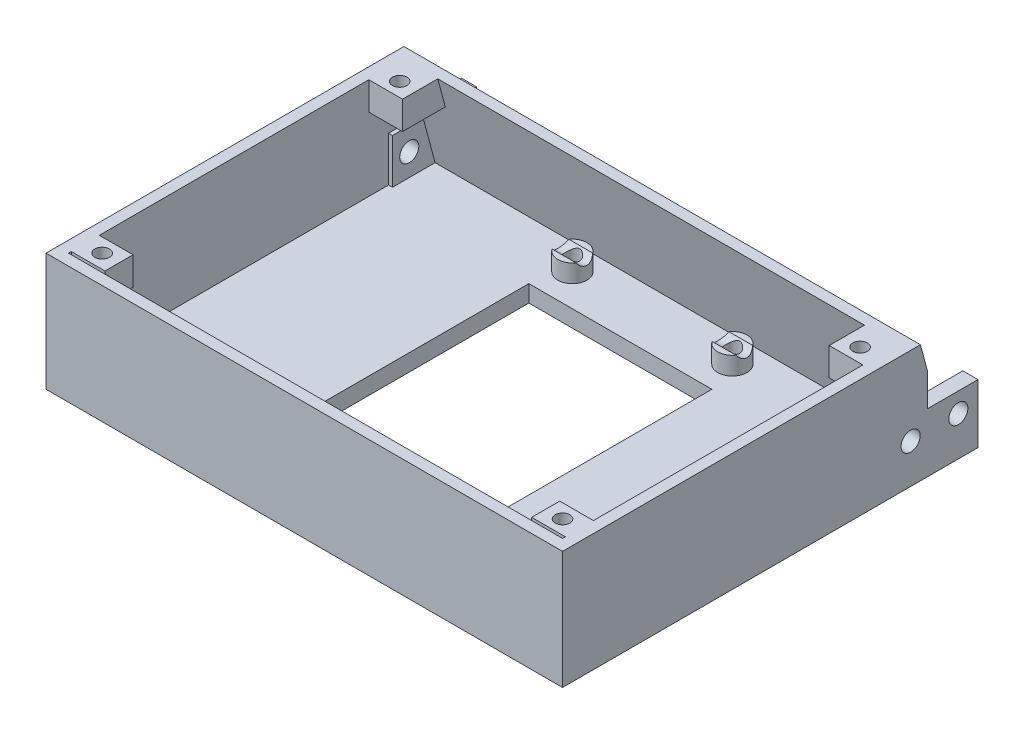
SolidWorks part; units mm, degrees
ref_plane "Спереди" through (0, 0, 0) normal (0, 0, 1) x (1, 0, 0)
ref_plane "Сверху" through (0, 0, 0) normal (0, 1, 0) x (1, 0, 0)
ref_plane "Справа" through (0, 0, 0) normal (1, 0, 0) x (0, 0, -1)
other "Configuration Table"
ref_plane "Плоскость1" through (0, 0, 55) normal (0, 0, 1) x (1, 0, 0)
sketch "Эскиз1" plane through (0, 0, 55) normal (0, 0, 1) x (1, 0, 0)
  line L1 (-46, -67) -> (46, -67)
  line L2 (-46, -67) -> (-46, -64)
  line L3 (-46, -64) -> (46, -64)
  line L4 (46, -67) -> (46, -64)
extrude "Front_panel_1" add sketch "Эскиз1" along normal blind 65
ref_plane "Плоскость2" through (0, -68, 0) normal (0, 1, 0) x (1, 0, 0)
sketch "Эскиз2" plane through (0, -68, 0) normal (0, 1, 0) x (1, 0, 0)
  line L1 (-16.3, -63.7) -> (16.3, -63.7)
  line L2 (-16.3, -63.7) -> (-16.3, -106.3)
  line L3 (-16.3, -106.3) -> (16.3, -106.3)
  line L4 (16.3, -63.7) -> (16.3, -106.3)
extrude "STEP_portrait_LCD_window_32_6x42_6_2" cut sketch "Эскиз2" along normal blind 5
ref_plane "Плоскость3" through (0, -68, 0) normal (0, 1, 0) x (1, 0, 0)
sketch "Эскиз3" plane through (0, -68, 0) normal (0, 1, 0) x (1, 0, 0)
  circle A0 centre (38, -77) radius 3.3
extrude "Button_bore_3" cut sketch "Эскиз3" along normal blind 5
ref_plane "Плоскость4" through (0, -64, 0) normal (0, 1, 0) x (1, 0, 0)
sketch "Эскиз4" plane through (0, -64, 0) normal (0, 1, 0) x (1, 0, 0)
  circle A0 centre (-14.25, -58) radius 2.6
  circle A1 centre (-14.25, -110) radius 2.6
  circle A2 centre (14.25, -58) radius 2.6
  circle A3 centre (14.25, -110) radius 2.6
extrude "Four_M3_PCB_standoffs_4" add sketch "Эскиз4" along normal blind 3.2
ref_plane "Плоскость5" through (0, -68, 0) normal (0, 1, 0) x (1, 0, 0)
sketch "Эскиз5" plane through (0, -68, 0) normal (0, 1, 0) x (1, 0, 0)
  circle A0 centre (-14.25, -58) radius 1.3
  circle A1 centre (14.25, -58) radius 1.3
  circle A2 centre (-14.25, -110) radius 1.3
  circle A3 centre (14.25, -110) radius 1.3
extrude "M3_PCB_mount_pilots_52x28_5_5" cut sketch "Эскиз5" along normal blind 9
ref_plane "Плоскость6" through (0, 0, 55) normal (0, 0, 1) x (1, 0, 0)
sketch "Эскиз6" plane through (0, 0, 55) normal (0, 0, 1) x (1, 0, 0)
  line L1 (-46, -64) -> (-44, -64)
  line L2 (-46, -64) -> (-46, -46)
  line L3 (-46, -46) -> (-44, -46)
  line L4 (-44, -64) -> (-44, -46)
extrude "Housing_left_6" add sketch "Эскиз6" along normal blind 65
ref_plane "Плоскость7" through (0, 0, 55) normal (0, 0, 1) x (1, 0, 0)
sketch "Эскиз7" plane through (0, 0, 55) normal (0, 0, 1) x (1, 0, 0)
  line L0 (46, -64) -> (-44, -64) construction
  line L1 (44, -64) -> (46, -64)
  line L2 (44, -64) -> (44, -46)
  line L3 (44, -46) -> (46, -46)
  line L4 (46, -64) -> (46, -46)
extrude "Housing_right_7" add sketch "Эскиз7" along normal blind 65
ref_plane "Плоскость8" through (0, 0, 55) normal (0, 0, 1) x (1, 0, 0)
sketch "Эскиз8" plane through (0, 0, 55) normal (0, 0, 1) x (1, 0, 0)
  line L1 (-44, -64) -> (44, -64)
  line L2 (-44, -64) -> (-44, -46)
  line L3 (-44, -46) -> (44, -46)
  line L4 (44, -64) -> (44, -46)
ref_plane "Плоскость9" through (0, 0, 118) normal (0, 0, 1) x (1, 0, 0)
sketch "Эскиз9" plane through (0, 0, 118) normal (0, 0, 1) x (1, 0, 0)
  line L1 (-44, -64) -> (44, -64)
  line L2 (-44, -64) -> (-44, -46)
  line L3 (-44, -46) -> (44, -46)
  line L4 (44, -64) -> (44, -46)
extrude "Housing_top_9" add sketch "Эскиз9" along normal blind 2
ref_plane "Плоскость10" through (0, 0, 55.5) normal (0, 0, 1) x (1, 0, 0)
sketch "Эскиз10" plane through (0, 0, 55.5) normal (0, 0, 1) x (1, 0, 0)
  line L0 (46, -46) -> (-46, -46) construction
  line L1 (-44, -51) -> (-38, -51)
  line L2 (-44, -51) -> (-44, -46)
  line L3 (-44, -46) -> (-38, -46)
  line L4 (-38, -51) -> (-38, -46)
extrude "Cover_post_LB_10" add sketch "Эскиз10" along normal blind 5
ref_plane "Плоскость11" through (0, 0, 55.5) normal (0, 0, 1) x (1, 0, 0)
sketch "Эскиз11" plane through (0, 0, 55.5) normal (0, 0, 1) x (1, 0, 0)
  line L1 (38, -51) -> (44, -51)
  line L2 (38, -51) -> (38, -46)
  line L3 (38, -46) -> (44, -46)
  line L4 (44, -51) -> (44, -46)
extrude "Cover_post_RB_11" add sketch "Эскиз11" along normal blind 5
ref_plane "Плоскость12" through (0, 0, 112.5) normal (0, 0, 1) x (1, 0, 0)
sketch "Эскиз12" plane through (0, 0, 112.5) normal (0, 0, 1) x (1, 0, 0)
  line L1 (-44, -51) -> (-38, -51)
  line L2 (-44, -51) -> (-44, -46)
  line L3 (-44, -46) -> (-38, -46)
  line L4 (-38, -51) -> (-38, -46)
extrude "Cover_post_LT_12" add sketch "Эскиз12" along normal blind 5
ref_plane "Плоскость13" through (0, 0, 112.5) normal (0, 0, 1) x (1, 0, 0)
sketch "Эскиз13" plane through (0, 0, 112.5) normal (0, 0, 1) x (1, 0, 0)
  line L1 (38, -51) -> (44, -51)
  line L2 (38, -51) -> (38, -46)
  line L3 (38, -46) -> (44, -46)
  line L4 (44, -51) -> (44, -46)
extrude "Cover_post_RT_13" add sketch "Эскиз13" along normal blind 5
ref_plane "Плоскость14" through (0, -52, 0) normal (0, 1, 0) x (1, 0, 0)
sketch "Эскиз14" plane through (0, -52, 0) normal (0, 1, 0) x (1, 0, 0)
  circle A0 centre (-41, -58) radius 1.3
  circle A1 centre (41, -58) radius 1.3
  circle A2 centre (-41, -115) radius 1.3
  circle A3 centre (41, -115) radius 1.3
ref_plane "Плоскость15" through (0, 0, 68) normal (0, 0, 1) x (1, 0, 0)
sketch "Эскиз15" plane through (0, 0, 68) normal (0, 0, 1) x (1, 0, 0)
  line L0 (50, -64) -> (-50, -64) construction
  line L1 (34, -64) -> (43, -64)
  line L2 (34, -64) -> (34, -56)
  line L3 (34, -56) -> (43, -56)
  line L4 (43, -64) -> (43, -56)
extrude "Button_lower_shelf_15" add sketch "Эскиз15" along normal blind 2
ref_plane "Плоскость16" through (0, 0, 84) normal (0, 0, 1) x (1, 0, 0)
sketch "Эскиз16" plane through (0, 0, 84) normal (0, 0, 1) x (1, 0, 0)
  line L0 (50, -64) -> (-50, -64) construction
  line L1 (34, -64) -> (43, -64)
  line L2 (34, -64) -> (34, -56)
  line L3 (34, -56) -> (43, -56)
  line L4 (43, -64) -> (43, -56)
extrude "Button_upper_shelf_16" add sketch "Эскиз16" along normal blind 2
ref_plane "Плоскость17" through (0, -65, 0) normal (0, 1, 0) x (1, 0, 0)
sketch "Эскиз17" plane through (0, -65, 0) normal (0, 1, 0) x (1, 0, 0)
  circle A0 centre (36, -69) radius 1.05
  circle A1 centre (41, -85) radius 1.05
extrude "Button_carrier_M2_pilots_17" cut sketch "Эскиз17" along normal blind 10
ref_plane "Плоскость18" through (0, 0, 46) normal (0, 0, 1) x (1, 0, 0)
sketch "Эскиз18" plane through (0, 0, 46) normal (0, 0, 1) x (1, 0, 0)
  line L0 (-46, -67) -> (46, -67) construction
  line L1 (43.3, -67) -> (46, -67)
  line L2 (43.3, -67) -> (43.3, -56.5)
  line L3 (43.3, -56.5) -> (46, -56.5)
  line L4 (46, -67) -> (46, -56.5)
  line L5 (46, -67) -> (46, -46) construction
extrude "Right_tilt_ear_18" add sketch "Эскиз18" along normal blind 15
ref_plane "Плоскость19" through (0, 0, 46) normal (0, 0, 1) x (1, 0, 0)
sketch "Эскиз19" plane through (0, 0, 46) normal (0, 0, 1) x (1, 0, 0)
  line L1 (-46, -67) -> (-43.3, -67)
  line L2 (-46, -67) -> (-46, -56)
  line L3 (-46, -56) -> (-43.3, -56)
  line L4 (-43.3, -67) -> (-43.3, -56)
extrude "Left_tilt_ear_19" add sketch "Эскиз19" along normal blind 15
ref_plane "Плоскость20" through (-47, 0, 0) normal (1, 0, 0) x (0, 0, -1)
sketch "Эскиз20" plane through (-47, 0, 0) normal (1, 0, 0) x (0, 0, -1)
  circle A0 centre (-49.5, -60) radius 1.7
  circle A1 centre (-58, -60) radius 1.7
extrude "M3_hinge_and_angle_lock_20" cut sketch "Эскиз20" along normal blind 94
ref_plane "Плоскость21" through (0, 0, 52) normal (0, 0, 1) x (1, 0, 0)
sketch "Эскиз21" plane through (0, 0, 52) normal (0, 0, 1) x (1, 0, 0)
  line L0 (46, -67) -> (46, -46) construction
  line L1 (-46, -67) -> (46, -67)
  line L2 (-46, -67) -> (-46, -64)
  line L3 (-46, -64) -> (46, -64)
  line L4 (46, -67) -> (46, -64)
extrude "Front_lower_extension_201" add sketch "Эскиз21" along normal blind 3
ref_plane "Плоскость22" through (-47, 0, 0) normal (1, 0, 0) x (0, 0, -1)
sketch "Эскиз22" plane through (-47, 0, 0) normal (1, 0, 0) x (0, 0, -1)
  line L0 (-10, -55) -> (-10, -40)
  line L1 (-10, -40) -> (-57.8613, -40)
  line L2 (-57.8613, -40) -> (-53.842, -55)
  line L3 (-53.842, -55) -> (-10, -55)
extrude "Housing_cage_roof_clearance_202" cut sketch "Эскиз22" along normal blind 94
ref_plane "Плоскость23" through (-44, 0, 0) normal (1, 0, 0) x (0, 0, -1)
sketch "Эскиз23" plane through (-44, 0, 0) normal (1, 0, 0) x (0, 0, -1)
  line L0 (-51.4305, -64) -> (-56.2536, -46)
  line L1 (-56.2536, -46) -> (-58.2206, -46)
  line L2 (-58.2206, -46) -> (-53.3975, -64)
  line L3 (-53.3975, -64) -> (-51.4305, -64)
extrude "Horizontal_enclosure_floor_203" add sketch "Эскиз23" along normal blind 88
ref_plane "Плоскость24" through (0, 0, 59.5) normal (0, 0, 1) x (1, 0, 0)
sketch "Эскиз24" plane through (0, 0, 59.5) normal (0, 0, 1) x (1, 0, 0)
  line L0 (-44, -64) -> (-44, -46) construction
  line L1 (-44, -51) -> (-38, -51)
  line L2 (-44, -51) -> (-44, -46)
  line L3 (-44, -46) -> (-38, -46)
  line L4 (-38, -51) -> (-38, -46)
extrude "Cover_lower_post_L_204" add sketch "Эскиз24" along normal blind 5
ref_plane "Плоскость25" through (0, 0, 59.5) normal (0, 0, 1) x (1, 0, 0)
sketch "Эскиз25" plane through (0, 0, 59.5) normal (0, 0, 1) x (1, 0, 0)
  line L1 (38, -51) -> (44, -51)
  line L2 (38, -51) -> (38, -46)
  line L3 (38, -46) -> (44, -46)
  line L4 (44, -51) -> (44, -46)
extrude "Cover_lower_post_R_205" add sketch "Эскиз25" along normal blind 5
ref_plane "Плоскость26" through (0, -52, 0) normal (0, 1, 0) x (1, 0, 0)
sketch "Эскиз26" plane through (0, -52, 0) normal (0, 1, 0) x (1, 0, 0)
  circle A0 centre (-41, -62) radius 1.3
  circle A1 centre (41, -62) radius 1.3
  circle A2 centre (-41, -115) radius 1.3
  circle A3 centre (41, -115) radius 1.3
extrude "Rear_cover_M3_pilots_final_206" cut sketch "Эскиз26" along normal blind 8
